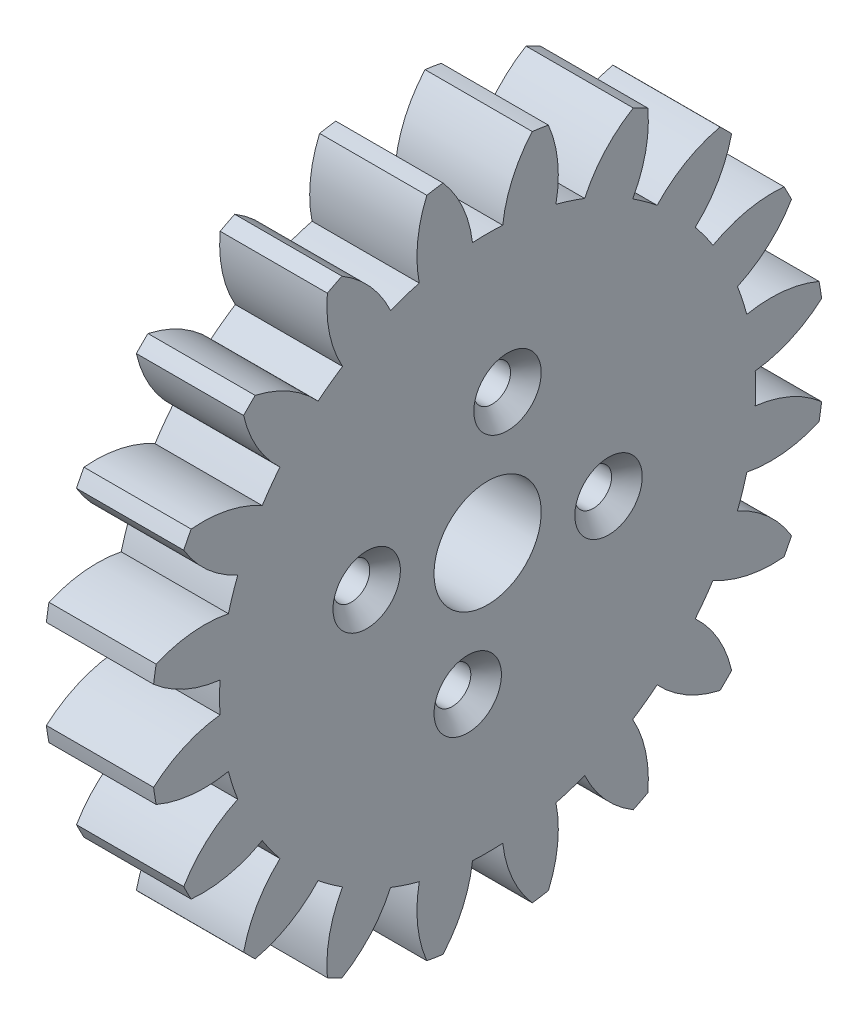
SolidWorks part; units mm, degrees
ref_plane "Plane1" through (0, 0, 0) normal (0, 0, 1) x (1, 0, 0)
ref_plane "Plane2" through (0, 0, 0) normal (0, 1, 0) x (1, 0, 0)
ref_plane "Plane3" through (0, 0, 0) normal (1, 0, 0) x (0, 0, -1)
sketch "HoldingSke" plane through (0, 0, 0) normal (0, 1, 0) x (1, 0, 0)
  line L0 (0, 0) -> (0.4698, -0.171)
  line L1 (-15, 0) -> (100, 0) construction
  line L2 (0, 0) -> (-2.1039, 2.3779)
  line L3 (0, 0) -> (-11.863, 4.5341)
  line L4 (0, 0) -> (8.1152, 2.9537)
  line L5 (0, 0) -> (-46.8476, -17.4728)
  line L6 (0, 0) -> (-5.8027, -3.9151)
  line L7 (-2.1039, 2.3779) -> (8.6586, 51.2059)
  line L8 (-76.2, 54.61) -> (-75.2, 54.61)
  line L9 (-71.009, 38.7566) -> (-53.1078, 45.2721)
  line L10 (-76.2, 71.12) -> (104.1128, 71.12)
  line L11 (0, 0) -> (-7, 0)
  line L12 (-76.2, 101.6) -> (-76.133, 101.6)
  line L13 (24.9733, 27.94) -> (52.9518, 28.4284)
  line L14 (24.9733, 27.94) -> (24.9743, 27.94)
  line L15 (24.9733, 27.94) -> (100.4006, 29.5858)
  line L16 (-63.627, -2) -> (-12.827, -2)
  circle A0 centre (0, 0) radius 3.5
  circle A1 centre (0, 0) radius 17.499
  circle A2 centre (0, 0) radius 37.5
  circle A3 centre (0, 0) radius 3.5
  dimension "MHD" = 34.998
  dimension "Hub_dia" = 75
  dimension "Bore" = 7
  dimension "MBD" = 7
  dimension "Num_teeth" = 20
  dimension "Pitch" = 0.5
  dimension "Overall_len" = 50
  dimension "Show_teeth" = 20
  dimension "Thickness" = 7
  dimension "OAL" = 50.0001
  dimension "T_dim" = 1
  dimension "Ap" = 20
  dimension "H" = 19.05
  dimension "Pitch_radius" = 180.3128
  dimension "Width" = 7
  dimension "Backlash" = 0.067
  dimension "Addendum_fac" = 1
  dimension "Dedendum_fac" = 1.25
  dimension "Clearance_fac" = 0.25
  dimension "Dedendum_add" = 0.001
  dimension "Module" = 2
sketch "BasProSke" plane through (0, 0, 0) normal (0, 1, 0) x (1, 0, 0)
  line L0 (-10, 0) -> (60, 0) construction
  line L1 (0, 0) -> (0, 22)
  line L2 (0, 0) -> (7, 0)
  line L3 (7, 0) -> (7, 22)
  line L4 (7, 22) -> (0, 22)
  dimension "Thickness" = 7
  dimension "Diameter" = 44
revolve "Base-Revolve" add sketch "BasProSke" angle 360 about L0
sketch "TooCutSke" plane through (0, 0, 0) normal (1, 0, 0) x (0, 0, -1)
  line L1 (0, 0) -> (0, 107) construction
  line L2 (0, 0) -> (-1.6864, 19.9288) construction
  line L3 (0, 0) -> (-6.2409, 39.4033) construction
  line L4 (-1.6864, 19.9288) -> (-3.1204, 19.7016) construction
  arc A0 (0.9862, 17.4712) -> (-0.9862, 17.4712) centre (0, 0) ccw
  arc A1 (2.9329, 21.8293) -> (-2.9329, 21.8293) centre (0, 0) ccw
  circle A2 centre (0, 0) radius 20 construction
  circle A3 centre (0, 0) radius 18.7939 construction
  arc A4 (-0.9862, 17.4712) -> (-2.9329, 21.8293) centre (-8.9313, 16.536) ccw
  arc A5 (2.9329, 21.8293) -> (0.9862, 17.4712) centre (8.9313, 16.536) ccw
  dimension "Root_dia" = 34.998
  dimension "Overcut_dia" = 44.0508
  dimension "Pitch_dia" = 40
  dimension "Base_dia" = 37.5877
  dimension "Flank_rad" = 8
  dimension "Half_ang" = 9
  dimension "Half_CT" = 1.4519
extrude "ToothCut" cut sketch "TooCutSke" along normal through all
fillet "Breaks" [suppressed] radius 0.04
fillet "RootFillets" [suppressed] radius 0.501
pattern_circular "TeethCuts" count 20 every 18 about axis through (-10, 0, 0) along (1, 0, 0) of "ToothCut", "RootFillets", "Breaks"
sketch "HubNeaOneSke" plane through (0, 0, 0) normal (-1, 0, 0) x (0, 0, 1)
  circle A0 centre (0, 0) radius 17.499
  dimension "Diameter" = 34.998
extrude "HubNearOne" [suppressed] add sketch "HubNeaOneSke" along normal blind 43.0001
sketch "HubNeaBotSke" plane through (0, 0, 0) normal (-1, 0, 0) x (0, 0, 1)
  circle A0 centre (0, 0) radius 17.499
  dimension "Diameter" = 34.998
extrude "HubNearBoth" [suppressed] add sketch "HubNeaBotSke" along normal blind 21.5
ref_plane "FarPln" through (7, 0, 0) normal (1, 0, 0) x (0, 0, -1)
sketch "HubFarSke" plane through (7, 0, 0) normal (1, 0, 0) x (0, 0, -1)
  circle A0 centre (0, 0) radius 17.499
  dimension "Diameter" = 34.998
extrude "HubFar" [suppressed] add sketch "HubFarSke" along normal blind 21.5
sketch "BorSke" plane through (0, 0, 0) normal (1, 0, 0) x (0, 0, -1)
  circle A0 centre (0, 0) radius 3.5
  dimension "Diameter" = 7
extrude "Bore" cut sketch "BorSke" along normal mid plane 100.0001
sketch "KeySke" plane through (0, 0, 0) normal (1, 0, 0) x (0, 0, -1)
  line L0 (-1, 0) -> (-1, 4.5)
  line L1 (-1, 4.5) -> (1, 4.5)
  line L2 (1, 4.5) -> (1, 0)
  line L3 (0, 0) -> (0, 34) construction
  line L4 (-1, 0) -> (1, 0)
  dimension "Offset" = 4.5
  dimension "Width" = 2
extrude "Keyway" [suppressed] cut sketch "KeySke" along normal mid plane 100.0001
pattern_circular "Keyway2" [suppressed] count 2 every 90 about axis through (-10, 0, 0) along (1, 0, 0)
sketch "Esquisse1" plane through (7, 0, 0) normal (1, 0, 0) x (0, 0, -1)
  circle A0 centre (0, 0) radius 8 construction
  circle A1 centre (1.298, 7.894) radius 0.5
  dimension "D1" = 16
  dimension "D2" = 1
hole_wizard "Fraisage pour vis à tête fraisée M21" positions "Esquisse2" profile "Esquisse3" countersink size "M2" standard "ISO" end condition up to next
sketch "Esquisse2" plane through (7, 0, 0) normal (1, 0, 0) x (0, 0, -1)
  point P0 (1.298, 7.894)
sketch "Esquisse3" plane through (7, 7.894, -1.298) normal (0, 1, 0) x (0, 0, -1)
  line L0 (0, 0) -> (0, 7)
  line L1 (0, 7) -> (1.2, 7)
  line L2 (1.2, 7) -> (1.2, 1)
  line L3 (1.2, 1) -> (2.2, 0)
  line L5 (2.2, 0) -> (0, 0)
  line L6 (-1.2, 1) -> (-2.2, 0) construction
  line L11 (0, -6.35) -> (0, 107.95) construction
  dimension "Diamètre du perçage jusqu'au prochain" = 2.4
  dimension "Profondeur du perçage jusqu'au prochain" = 7
  dimension "Diamètre du fraisage entrant" = 4.4
  dimension "Angle du fraisage entrant" = 90
pattern_circular "Répétition circulaire1" count 4 over 360 about axis through (0, 0, 0) along (1, 0, 0) of "Fraisage pour vis à tête fraisée M21"
equation "' \"Module@HoldingSke\" = 6.35"
equation "' \"Num_teeth@HoldingSke\" = 12"
equation "' \"Ap@HoldingSke\" =  20"
equation "' \"Ap@HoldingSke\" = 20"
equation "' \"Width@HoldingSke\" = 0.5 * 25.4"
equation "' \"Hub_dia@HoldingSke\"= 1 * 25.4"
equation "' \"Hub_dia@HoldingSke\" = 1 * 25.4"
equation "' \"Overall_len@HoldingSke\" = 1.0 * 25.4"
equation "' \"Bore@HoldingSke\" = 0.75 * 25.4"
equation "' \"T_dim@HoldingSke\" = 0.1 * 25.4"
equation "' \"Width@KeySke\" = 0.25 * 25.4"
equation "' \"Show_teeth@HoldingSke\" = 13"
equation "' \"Backlash@HoldingSke\" = 0.009 * 25.4"
equation "' \"Addendum_fac@HoldingSke\" = 1.0"
equation "' \"Dedendum_fac@HoldingSke\" = 1.25"
equation "' \"Dedendum_add@HoldingSke\" = 0.00005 * 25.4"
equation "' \"Clearance_fac@HoldingSke\" = 0.25"
equation "\"Pitch@HoldingSke\" = 1 / \"Module@HoldingSke\""
equation "\"Overcut_dia@TooCutSke\" = (\"Num_teeth@HoldingSke\" + 2 * \"Addendum_fac@HoldingSke\") / \"Pitch@HoldingSke\" + 0.002 * 25.4"
equation "\"Pitch_dia@TooCutSke\" = \"Num_teeth@HoldingSke\" / \"Pitch@HoldingSke\""
equation "\"Base_dia@TooCutSke\" = \"Num_teeth@HoldingSke\" / \"Pitch@HoldingSke\" * cos((\"Ap@HoldingSke\"  * 3.14159265 / 180))"
equation "\"Root_dia@TooCutSke\" = (\"Num_teeth@HoldingSke\" + 2) / \"Pitch@HoldingSke\" - 2 * (\"Addendum_fac@HoldingSke\" + \"Dedendum_fac@HoldingSke\") / \"Pitch@HoldingSke\" - \"Dedendum_add@HoldingSke\" * 2"
equation "\"Half_ang@TooCutSke\" = 180 / \"Num_teeth@HoldingSke\""
equation "\"Half_CT@TooCutSke\" = \"Num_teeth@HoldingSke\" / \"Pitch@HoldingSke\" * sin((3.14159265 / 2 / \"Num_teeth@HoldingSke\")) / 2 - 7 * \"Backlash@HoldingSke\" / 4"
equation "\"Flank_rad@TooCutSke\" = \"Num_teeth@HoldingSke\" / \"Pitch@HoldingSke\" / 5"
equation "\"Radius@RootFillets\" = \"Clearance_fac@HoldingSke\" / \"Pitch@HoldingSke\" + \"Dedendum_add@HoldingSke\""
equation "\"Break_rad@Breaks\" = 0.02 / \"Pitch@HoldingSke\""
equation "\"Thickness@HoldingSke\" = \"Width@HoldingSke\""
equation "\"OAL@HoldingSke\" = \"Thickness@HoldingSke\""
equation "\"MHD@HoldingSke\" = (\"Num_teeth@HoldingSke\" + 2) / \"Pitch@HoldingSke\" - 2 * (\"Addendum_fac@HoldingSke\" + \"Dedendum_fac@HoldingSke\")  / \"Pitch@HoldingSke\" - \"Dedendum_add@HoldingSke\" * 2"
equation "\"MBD@HoldingSke\" = (\"Num_teeth@HoldingSke\" + 2) / \"Pitch@HoldingSke\" - 2 * (\"Addendum_fac@HoldingSke\" + \"Dedendum_fac@HoldingSke\")  / \"Pitch@HoldingSke\" - \"Dedendum_add@HoldingSke\" * 2 - 0.002 * 25.4"
equation "\"MHD@HoldingSke\" = ((sgn( \"MHD@HoldingSke\" - \"Hub_dia@HoldingSke\" )-1)*( \"MHD@HoldingSke\" - \"Hub_dia@HoldingSke\" ))/-2+ \"Hub_dia@HoldingSke\""
equation "\"MBD@HoldingSke\" = ((sgn( \"MBD@HoldingSke\" - \"Bore@HoldingSke\" )-1)*( \"MBD@HoldingSke\" - \"Bore@HoldingSke\" ))/-2+ \"Bore@HoldingSke\""
equation "\"OAL@HoldingSke\" = ((sgn( \"OAL@HoldingSke\" - \"Overall_len@HoldingSke\" )+1)*( \"OAL@HoldingSke\" - \"Overall_len@HoldingSke\" ))/2 + \"Overall_len@HoldingSke\" + 0.000002 * 25.4"
equation "\"Num_teeth@TeethCuts\" = int( \"Show_teeth@HoldingSke\" ) + 1"
equation "\"Num_teeth@TeethCuts\" = ((sgn( \"Num_teeth@TeethCuts\" - \"Num_teeth@HoldingSke\" )-1)*( \"Num_teeth@TeethCuts\" - \"Num_teeth@HoldingSke\" ))/-2+ \"Num_teeth@HoldingSke\""
equation "\"Num_teeth@TeethCuts\" = ((sgn( \"Num_teeth@TeethCuts\" - 2.0)+1)*( \"Num_teeth@TeethCuts\" - 2.0))/2 +2.0"
equation "\"Angle@TeethCuts\" = 360.0 / \"Num_teeth@HoldingSke\""
equation "\"Diameter@BasProSke\" = (\"Num_teeth@HoldingSke\" + 2 * \"Addendum_fac@HoldingSke\") / \"Pitch@HoldingSke\""
equation "\"Thickness@BasProSke\"  = \"Thickness@HoldingSke\""
equation "' \"Fillet_rad@BasProSke\" =  \"Thickness@HoldingSke\" * 0.05"
equation "' \"Fillet_rad@BasProSke\" = \"Thickness@HoldingSke\" * 0.05"
equation "\"MHD@HoldingSke\" = ((sgn( \"MHD@HoldingSke\" - \"Root_dia@TooCutSke\" )-1)*( \"MHD@HoldingSke\" - \"Root_dia@TooCutSke\" ))/-2+ \"Root_dia@TooCutSke\""
equation "\"Diameter@HubNeaOneSke\" = \"MHD@HoldingSke\""
equation "\"Length@HubNearOne\" = \"OAL@HoldingSke\" - \"Thickness@BasProSke\""
equation "\"Diameter@HubNeaBotSke\" = \"MHD@HoldingSke\""
equation "\"Length@HubNearBoth\" = ( \"OAL@HoldingSke\" - \"Thickness@BasProSke\" ) / 2.0"
equation "\"Thickness@FarPln\" = \"Thickness@BasProSke\""
equation "\"Diameter@HubFarSke\" = \"MHD@HoldingSke\""
equation "\"Length@HubFar\" = ( \"OAL@HoldingSke\" - \"Thickness@BasProSke\" ) / 2.0"
equation "\"Diameter@BorSke\" = \"MBD@HoldingSke\""
equation "\"D1@Bore\" = \"OAL@HoldingSke\" * 2.0"
equation "\"D1@Keyway\" = \"OAL@HoldingSke\" * 2.0"
equation "\"Offset@KeySke\" = \"T_dim@HoldingSke\" + \"MBD@HoldingSke\" / 2.0"
